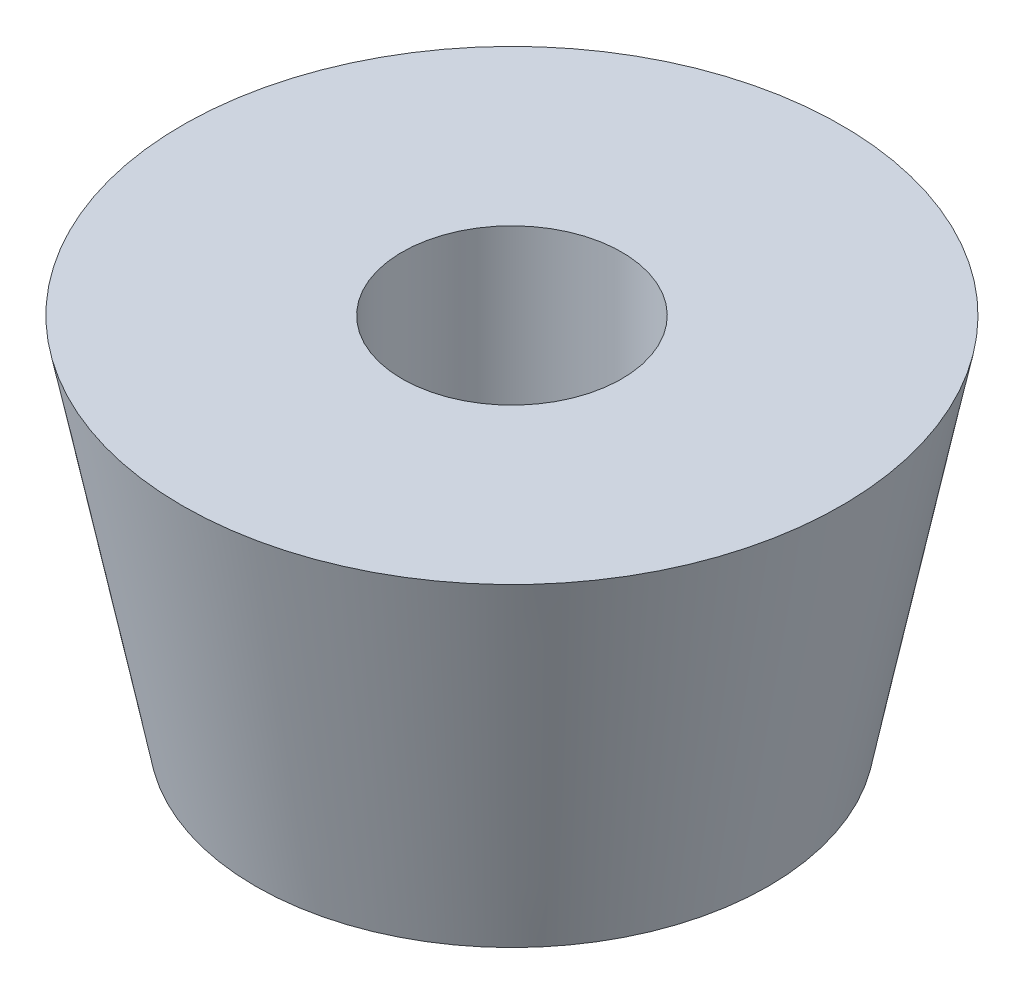
SolidWorks part; units mm, degrees
material "Brass"
ref_plane "Front Plane" through (0, 0, 0) normal (0, 0, 1) x (1, 0, 0)
ref_plane "Top Plane" through (0, 0, 0) normal (0, 1, 0) x (1, 0, 0)
ref_plane "Right Plane" through (0, 0, 0) normal (1, 0, 0) x (0, 0, -1)
sketch "Sketch1" plane through (0, 0, 0) normal (1, 0, 0) x (0, 0, -1)
  line L0 (6, 0) -> (6, -20)
  line L1 (6, -20) -> (14, -20)
  line L2 (14, -20) -> (18, 0)
  line L3 (18, 0) -> (6, 0)
  line L4 (0, 0) -> (0, -7.7304) construction
  dimension "D1" = 20
  dimension "D2" = 8
  dimension "D3" = 6
  dimension "D4" = 12
revolve "Revolve1" add sketch "Sketch1" angle 360 about L4
